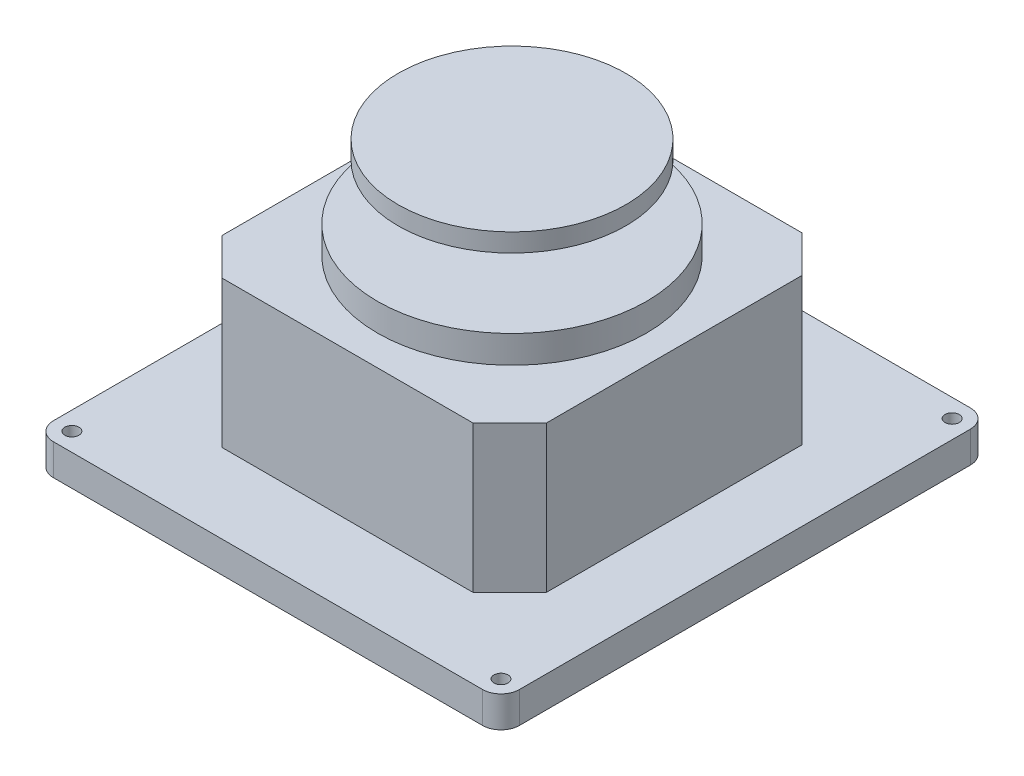
SolidWorks part; units mm, degrees
ref_plane "Plan de face" through (0, 0, 0) normal (0, 0, 1) x (1, 0, 0)
ref_plane "Plan de dessus" through (0, 0, 0) normal (0, 1, 0) x (1, 0, 0)
ref_plane "Plan de droite" through (0, 0, 0) normal (1, 0, 0) x (0, 0, -1)
sketch "Esquisse1" plane through (0, 0, 0) normal (0, 1, 0) x (1, 0, 0)
  line L1 (-8.85, 8.975) -> (8.85, 8.975)
  line L2 (-8.85, 8.975) -> (-8.85, -8.975)
  line L3 (-8.85, -8.975) -> (8.85, -8.975)
  line L4 (8.85, 8.975) -> (8.85, -8.975)
  line L5 (-8.85, 8.975) -> (8.85, -8.975) construction
  line L6 (-8.85, -8.975) -> (8.85, 8.975) construction
  point P0 (0, 0)
  dimension "D1" = 17.95
  dimension "D2" = 17.7
extrude "Boss.-Extru.1" add sketch "Esquisse1" along normal blind 8
sketch "Esquisse2" plane through (0, 8, 0) normal (0, 1, 0) x (1, 0, 0)
  line L0 (-8.85, -8.975) -> (-8.85, -6.975) construction
  line L1 (-8.85, 8.975) -> (-8.85, -8.975) construction
  line L2 (-8.85, -8.975) -> (-6.85, -8.975) construction
  line L3 (-8.85, -8.975) -> (8.85, -8.975) construction
  line L4 (-8.85, -6.975) -> (-6.85, -8.975)
  line L5 (-6.85, -8.975) -> (-8.85, -8.975)
  line L6 (-8.85, -8.975) -> (-8.85, -6.975)
  dimension "D1" = 2
  dimension "D2" = 2
extrude "Enlèv. mat.-Extru.1" cut sketch "Esquisse2" against normal blind 8
mirror "Symétrie1" about plane through (0, 0, 0) normal (0, 0, 1) of "Enlèv. mat.-Extru.1" second plane through (0, 0, 0) second plane normal (1, 0, 0)
sketch "Esquisse4" plane through (0, 8, 0) normal (0, 1, 0) x (1, 0, 0)
  circle A0 centre (0, 0) radius 7.335
extrude "Boss.-Extru.2" add sketch "Esquisse4" along normal blind 1.5
sketch "Esquisse5" plane through (0, 9.5, 0) normal (0, 1, 0) x (1, 0, 0)
  circle A0 centre (0, 0) radius 1.475
  dimension "D1" = 2.95
extrude "Boss.-Extru.3" add sketch "Esquisse5" along normal blind 3
ref_plane "Plan2" through (0, 12.5, 0) normal (0, 1, 0) x (1, 0, 0)
sketch "Esquisse6" plane through (0, 12.5, 0) normal (0, 1, 0) x (1, 0, 0)
  circle A0 centre (0, 0) radius 6.2085
extrude "Boss.-Extru.4" add sketch "Esquisse6" along normal blind 1
sketch "Esquisse7" plane through (0, 0, 0) normal (0, -1, 0) x (1, 0, 0)
  line L1 (-12.7, 13.3) -> (12.7, 13.3)
  line L2 (-12.7, 13.3) -> (-12.7, -13.3)
  line L3 (-12.7, -13.3) -> (12.7, -13.3)
  line L4 (12.7, 13.3) -> (12.7, -13.3)
  line L5 (-12.7, 13.3) -> (12.7, -13.3) construction
  line L6 (-12.7, -13.3) -> (12.7, 13.3) construction
  point P0 (0, 0)
  dimension "D1" = 25.4
  dimension "D2" = 26.6
extrude "Boss.-Extru.5" add sketch "Esquisse7" along normal blind 1.7
fillet "Congé1" radius 1 1 edges at (12.7, -0.85, 13.3)
fillet "Congé2" radius 1 3 edges at (-12.7, -0.85, 13.3) (-12.7, -0.85, -13.3) (12.7, -0.85, -13.3)
sketch "Esquisse8" plane through (0, -1.7, 0) normal (0, -1, 0) x (1, 0, 0)
  circle A0 centre (-11.7, -12.3) radius 0.3849
extrude "Enlèv. mat.-Extru.2" cut sketch "Esquisse8" against normal blind 1.7
mirror "Symétrie5" about plane through (0, 0, 0) normal (0, 0, 1) of "Enlèv. mat.-Extru.2" second plane through (0, 0, 0) second plane normal (1, 0, 0)
